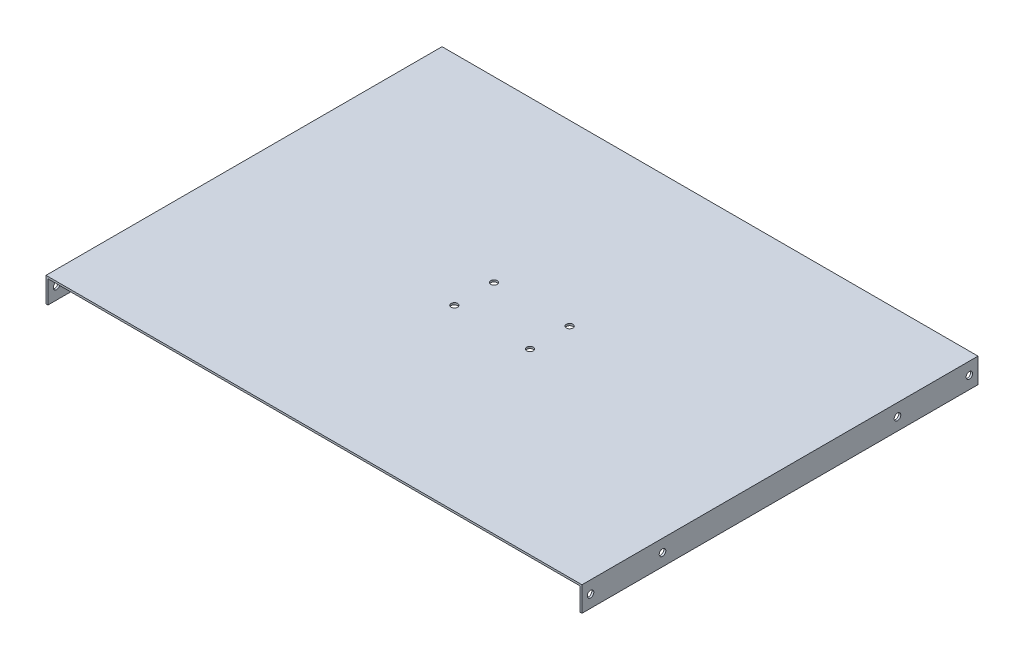
SolidWorks part; units mm, degrees
ref_plane "Plano frontal" through (0, 0, 0) normal (0, 0, 1) x (1, 0, 0)
ref_plane "Plano superior" through (0, 0, 0) normal (0, 1, 0) x (1, 0, 0)
ref_plane "Plano direito" through (0, 0, 0) normal (1, 0, 0) x (0, 0, -1)
sketch "Esboço1" plane through (0, 0, 0) normal (0, 1, 0) x (1, 0, 0)
  line L1 (-162.4, -120) -> (162.4, -120)
  line L2 (-162.4, -120) -> (-162.4, 120)
  line L3 (-162.4, 120) -> (162.4, 120)
  line L4 (162.4, -120) -> (162.4, 120)
  line L5 (-162.4, -120) -> (162.4, 120) construction
  line L6 (-162.4, 120) -> (162.4, -120) construction
  point P0 (0, 0)
  dimension "D1" = 324.8
  dimension "D2" = 240
extrude "Ressalto-extrusão1" add sketch "Esboço1" along normal blind 15
sketch "Esboço2" plane through (0, 0, 0) normal (0, 1, 0) x (1, 0, 0)
  line L0 (162.4, 120) -> (-162.4, 120) construction
  line L1 (-161.2, -120) -> (161.2, -120)
  line L2 (-161.2, -120) -> (-161.2, 120)
  line L3 (-161.2, 120) -> (161.2, 120)
  line L4 (161.2, -120) -> (161.2, 120)
  line L5 (-161.2, -120) -> (161.2, 120) construction
  line L6 (-161.2, 120) -> (161.2, -120) construction
  point P0 (0, 0)
  dimension "D1" = 322.4
extrude "Corte-extrusão1" cut sketch "Esboço2" along normal blind 13.8
sketch "Esboço3" plane through (0, 0, 0) normal (0, 1, 0) x (1, 0, 0)
  line L0 (-162.4, 120) -> (-162.4, -120) construction
  line L1 (-162.4, -120) -> (162.4, -120) construction
  line L2 (0, 0) -> (-187.3625, 0) construction
  line L3 (-187.3625, 0) -> (0, 0) construction
  line L4 (0, 0) -> (0, -129.0808) construction
  circle A0 centre (-22.92, -12) radius 2
  circle A1 centre (22.92, -12) radius 2
  circle A2 centre (22.92, 12) radius 2
  circle A3 centre (-22.92, 12) radius 2
  dimension "D3" = 4
  dimension "D1" = 139.48
  dimension "D2" = 108
extrude "Corte-extrusão2" cut sketch "Esboço3" along normal blind 13.8 from offset 10 contours A3 | A2 | A1 | A0
sketch "Esboço4" plane through (0, 0, 0) normal (1, 0, 0) x (0, 0, -1)
  line L0 (120, 15) -> (120, 0) construction
  line L1 (0, 31.5048) -> (0, -18.2642) construction
  circle A0 centre (114.8, 7.5) radius 2
  circle A1 centre (71.2, 7.5) radius 2
  circle A2 centre (-114.8, 7.5) radius 2
  circle A3 centre (-71.2, 7.5) radius 2
  dimension "D3" = 4
  dimension "D4" = 4
  dimension "D1" = 5.2
  dimension "D2" = 43.6
extrude "Corte-extrusão3" cut sketch "Esboço4" against normal blind 170 and the other way blind 170
